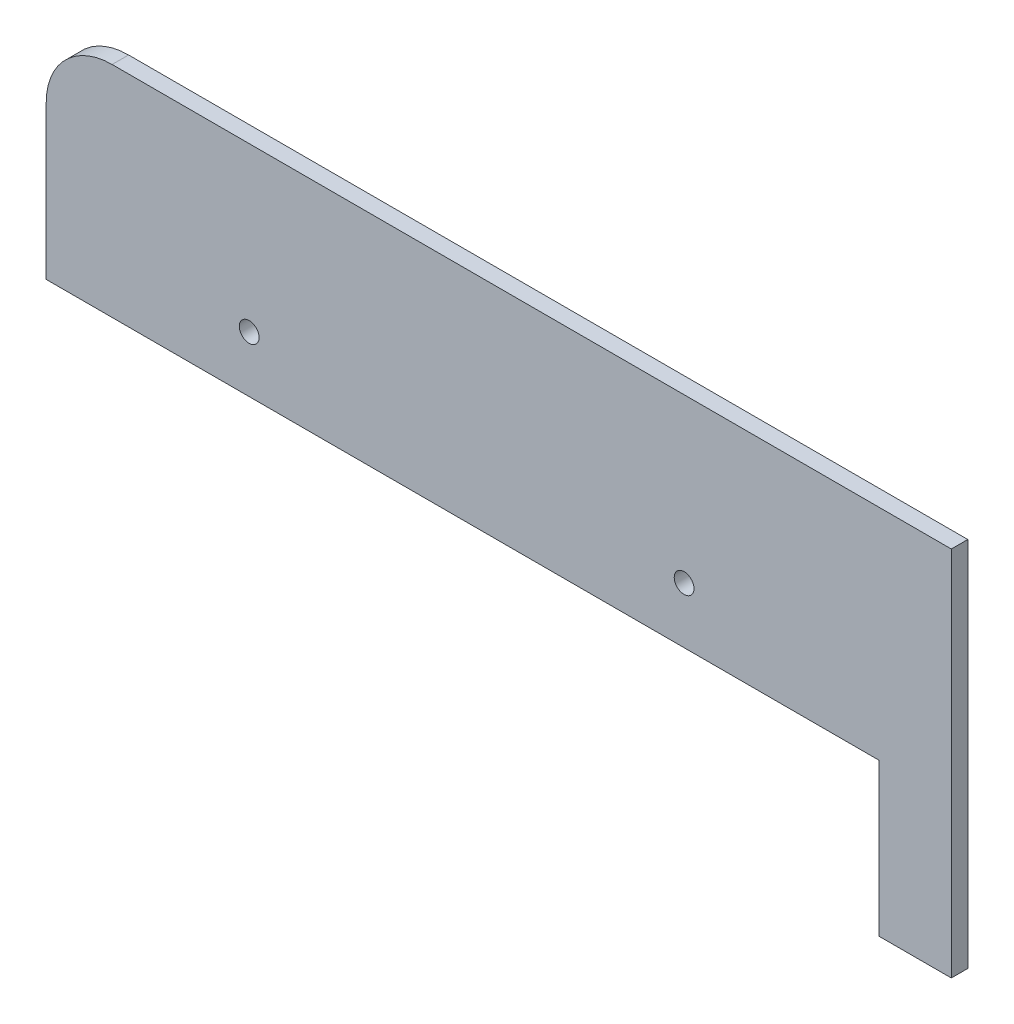
SolidWorks part; units mm, degrees
ref_plane "Front Plane" through (0, 0, 0) normal (0, 0, 1) x (1, 0, 0)
ref_plane "Top Plane" through (0, 0, 0) normal (0, 1, 0) x (1, 0, 0)
ref_plane "Right Plane" through (0, 0, 0) normal (1, 0, 0) x (0, 0, -1)
sketch "Sketch1" plane through (0, 0, 0) normal (0, 0, 1) x (1, 0, 0)
  line L0 (-67.4022, 38.8606) -> (-67.4022, 4.6106)
  line L1 (-67.4022, 38.8606) -> (67.9478, 38.8606)
  line L2 (-67.4022, 4.6106) -> (56.9378, 4.6106)
  line L3 (67.9478, 38.8606) -> (67.9478, -17.5194)
  line L4 (56.9378, 4.6106) -> (56.9378, -17.5194)
  line L5 (56.9378, -17.5194) -> (67.9478, -17.5194)
  dimension "D1" = 34.25
  dimension "D2" = 135.35
  dimension "D3" = 124.34
  dimension "D4" = 56.38
extrude "Boss-Extrude1" add sketch "Sketch1" along normal blind 2.5
sketch "Sketch2" plane through (0, 0, 0) normal (0, 0, -1) x (-1, 0, 0)
  line L0 (67.4022, 4.6106) -> (-56.9378, 4.6106) construction
  circle A0 centre (-27.3991, 14.1106) radius 1.5
  circle A1 centre (38.6009, 14.1106) radius 1.5
  dimension "D1" = 9.5
  dimension "D2" = 66
  dimension "D3" = 9.5
extrude "Cut-Extrude1" cut sketch "Sketch2" against normal blind 10
sketch "Sketch3" plane through (0, 4.6106, 0) normal (0, -1, 0) x (1, 0, 0)
  line L4 (-67.4022, 0) -> (56.9378, 0)
  line L5 (56.9378, 0) -> (56.9378, 2.5)
  line L6 (56.9378, 2.5) -> (-67.4022, 2.5)
  line L7 (-67.4022, 2.5) -> (-67.4022, 0)
  line L8 (-67.4022, 0) -> (56.9378, 0)
  line L9 (56.9378, 0) -> (56.9378, 2.5)
  line L10 (56.9378, 2.5) -> (-67.4022, 2.5)
  line L11 (-67.4022, 2.5) -> (-67.4022, 0)
  dimension "D1" = 0
extrude "Cut-Extrude2" cut sketch "Sketch3" against normal blind 1
sketch "Sketch4" plane through (-67.4022, 0, 0) normal (-1, 0, 0) x (0, 0, 1)
  line L4 (0, 5.6106) -> (2.5, 5.6106)
  line L5 (2.5, 5.6106) -> (2.5, 38.8606)
  line L6 (2.5, 38.8606) -> (0, 38.8606)
  line L7 (0, 38.8606) -> (0, 5.6106)
  line L8 (0, 5.6106) -> (2.5, 5.6106)
  line L9 (2.5, 5.6106) -> (2.5, 38.8606)
  line L10 (2.5, 38.8606) -> (0, 38.8606)
  line L11 (0, 38.8606) -> (0, 5.6106)
  dimension "D1" = 0
extrude "Boss-Extrude2" add sketch "Sketch4" along normal blind 2 contours L11 L8 L9 L10
fillet "Fillet2" radius 10 1 edges at (-69.4022, 38.8606, 1.25)
